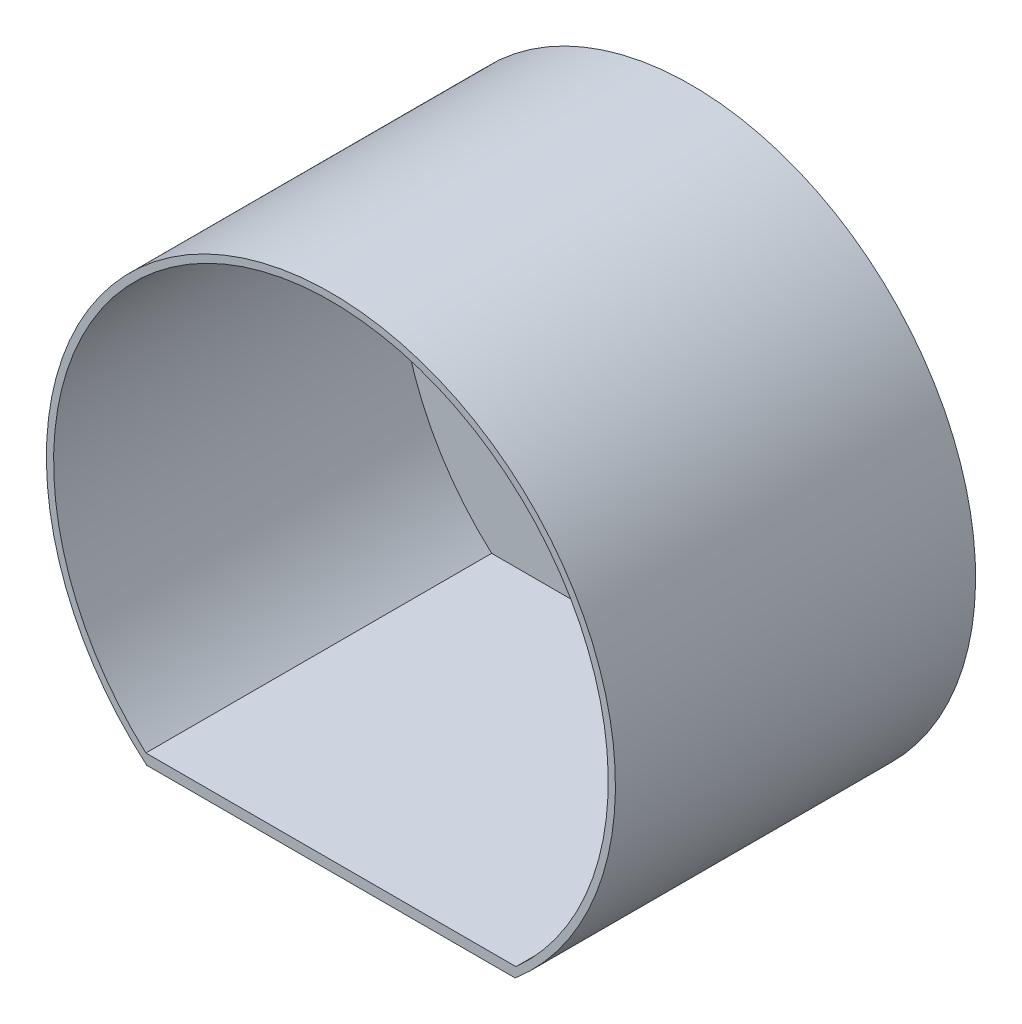
SolidWorks part; units mm, degrees
ref_plane "Front Plane" through (0, 0, 0) normal (0, 0, 1) x (1, 0, 0)
ref_plane "Top Plane" through (0, 0, 0) normal (0, 1, 0) x (1, 0, 0)
ref_plane "Right Plane" through (0, 0, 0) normal (1, 0, 0) x (0, 0, -1)
sketch "Sketch1" plane through (0, 0, 0) normal (0, 0, 1) x (1, 0, 0)
  line L0 (-25.577, -30.101) -> (25.577, -30.101)
  line L1 (-25.6871, -28.6779) -> (25.6871, -28.6779)
  arc A0 (25.6871, -28.6779) -> (-25.6871, -28.6779) centre (0, 0) ccw
  arc A1 (25.577, -30.101) -> (-25.577, -30.101) centre (0, 0) ccw
  dimension "D1" = 77
  dimension "D2" = 79
extrude "Boss-Extrude1" add sketch "Sketch1" along normal blind 50
sketch "Sketch2" plane through (0, 0, 0) normal (0, 0, -1) x (-1, 0, 0)
  line L0 (25.6871, -28.6779) -> (-25.6871, -28.6779) construction
  line L1 (25.6871, -28.6779) -> (-25.6871, -28.6779)
  arc A0 (25.6871, -28.6779) -> (-25.6871, -28.6779) centre (0, 0) ccw construction
  arc A1 (25.6871, -28.6779) -> (-25.6871, -28.6779) centre (0, 0) ccw
extrude "Boss-Extrude2" add sketch "Sketch2" against normal blind 2
sketch "Sketch3" plane through (0, 0, 0) normal (0, 0, -1) x (-1, 0, 0)
  circle A2 centre (0, 0) radius 6
  dimension "D1" = 12
extrude "Cut-Extrude1" cut sketch "Sketch3" against normal up to surface (2 mm away) up to face at (0, 4.911, 2)
sketch "Sketch4" plane through (0, 0, 0) normal (0, 0, -1) x (-1, 0, 0)
  line L0 (0, -28.6779) -> (0, 38) construction
  circle A0 centre (0, 18) radius 6
  dimension "D1" = 12
  dimension "D2" = 18
extrude "Cut-Extrude2" cut sketch "Sketch4" against normal up to surface (2 mm away) contours A0 up to face at (-6, 0, 2)
sketch "Sketch5" plane through (0, 0, 0) normal (0, 0, -1) x (-1, 0, 0)
  circle A0 centre (0, 0) radius 6 construction
  circle A1 centre (0, 0) radius 6
  circle A2 centre (0, 0) radius 9
  dimension "D1" = 3
extrude "Boss-Extrude3" add sketch "Sketch5" along normal blind 20
